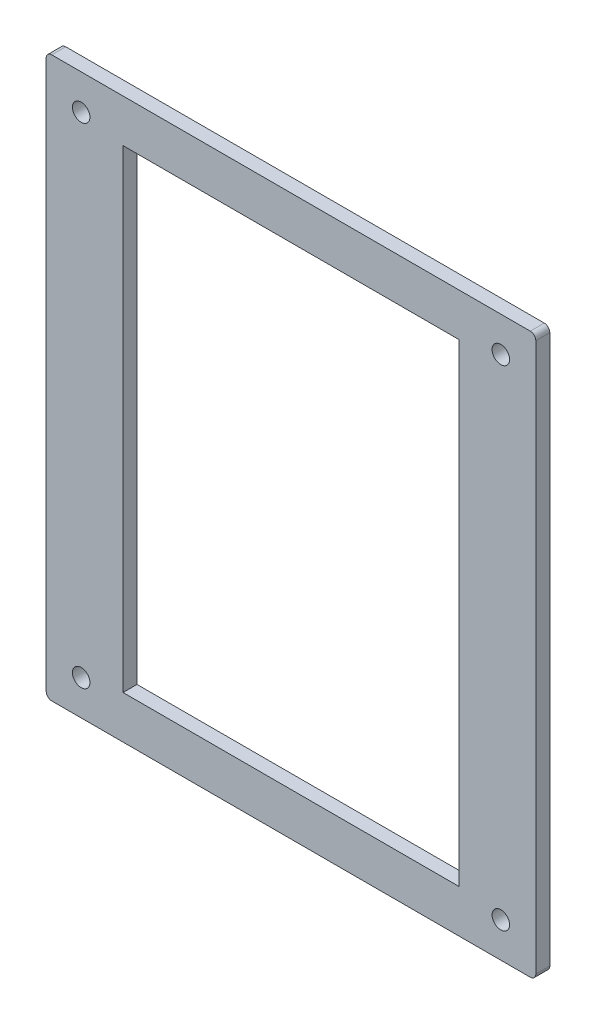
SolidWorks part; units mm, degrees
material "6061 Alloy"
ref_plane "Front Plane" through (0, 0, 0) normal (0, 0, 1) x (1, 0, 0)
ref_plane "Top Plane" through (0, 0, 0) normal (0, 1, 0) x (1, 0, 0)
ref_plane "Right Plane" through (0, 0, 0) normal (1, 0, 0) x (0, 0, -1)
sketch "Sketch1" plane through (0, 0, 0) normal (0, 0, 1) x (1, 0, 0)
  line L0 (82.55, -6.35) -> (6.35, -6.35) construction
  line L1 (0, 0) -> (88.9, 0)
  line L2 (0, 0) -> (0, -101.6)
  line L3 (0, -101.6) -> (88.9, -101.6)
  line L4 (88.9, 0) -> (88.9, -101.6)
  line L5 (13.95, -7.8) -> (74.95, -7.8)
  line L6 (13.95, -7.8) -> (13.95, -93.8)
  line L7 (13.95, -93.8) -> (74.95, -93.8)
  line L8 (74.95, -7.8) -> (74.95, -93.8)
  line L9 (6.35, -6.35) -> (6.35, -95.25) construction
  line L10 (6.35, -95.25) -> (82.55, -95.25) construction
  line L11 (82.55, -95.25) -> (82.55, -6.35) construction
  circle A0 centre (6.35, -6.35) radius 1.59
  circle A1 centre (82.55, -6.35) radius 1.59
  circle A2 centre (6.35, -95.25) radius 1.59
  circle A3 centre (82.55, -95.25) radius 1.59
  point P11 (44.45, 0)
  point P12 (44.45, -7.8)
  point P13 (74.95, -50.8)
  point P14 (88.9, -50.8)
  point P21 (44.45, -6.35)
  point P22 (82.55, -50.8)
  dimension "D7" = 3.18
  dimension "D1" = 61
  dimension "D2" = 86
  dimension "D3" = 76.2
  dimension "D4" = 88.9
  dimension "D5" = 6.35
  dimension "D6" = 6.35
  dimension "D8" = 88.9
  dimension "D9" = 101.6
extrude "Boss-Extrude1" add sketch "Sketch1" along normal blind 2.54
fillet "Fillet1" radius 1 4 edges at (0, -101.6, 1.27) (88.9, -101.6, 1.27) (88.9, 0, 1.27) (0, 0, 1.27)
equation "\"D6@Sketch1\"=\"D5@Sketch1\""
equation "\"D3@Sketch1\"=3.0*25.4"
equation "\"D4@Sketch1\"=3.5*25.4"
